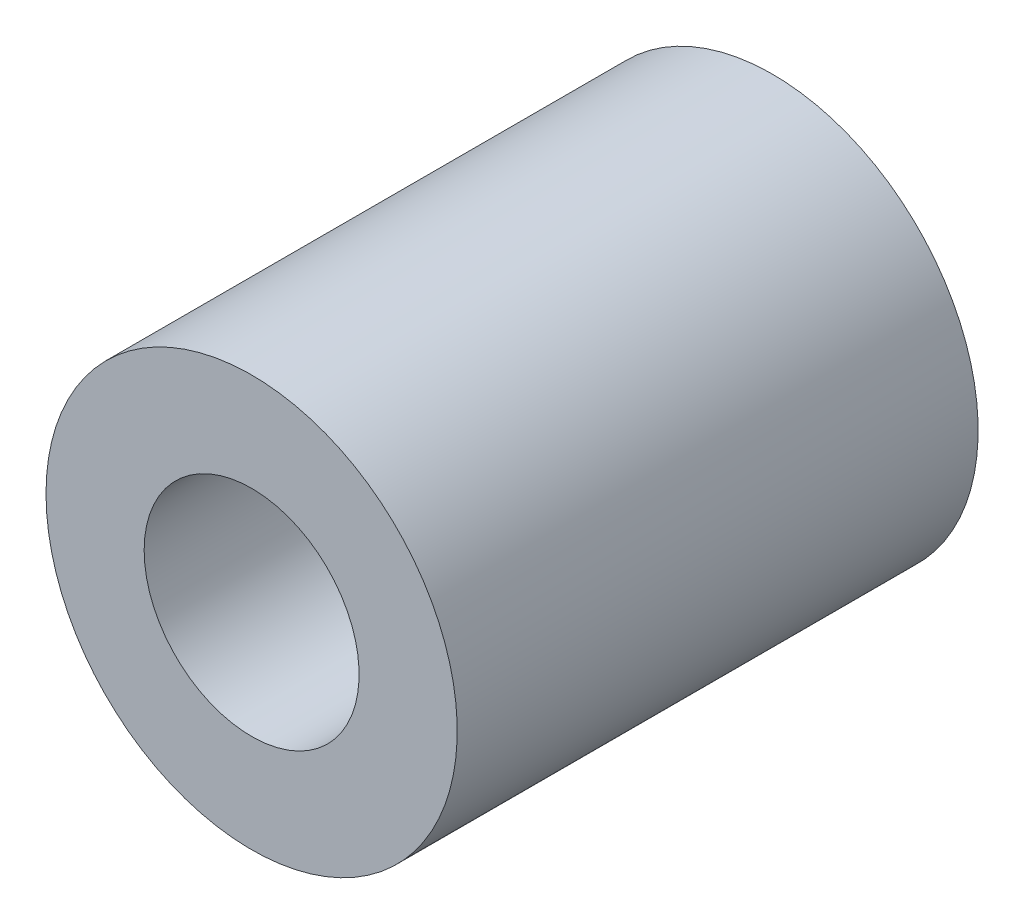
SolidWorks part; units mm, degrees
material "6061-T6 (SS)"
ref_plane "Front Plane" through (0, 0, 0) normal (0, 0, 1) x (1, 0, 0)
ref_plane "Top Plane" through (0, 0, 0) normal (0, 1, 0) x (1, 0, 0)
ref_plane "Right Plane" through (0, 0, 0) normal (1, 0, 0) x (0, 0, -1)
sketch "Sketch1" plane through (0, 0, 0) normal (0, 0, 1) x (1, 0, 0)
  circle A0 centre (0, 0) radius 2.4892
  circle A1 centre (0, 0) radius 4.7625
  dimension "D1" = 9.525
  dimension "D2" = 4.9784
extrude "Boss-Extrude1" add sketch "Sketch1" along normal mid plane 12.065
